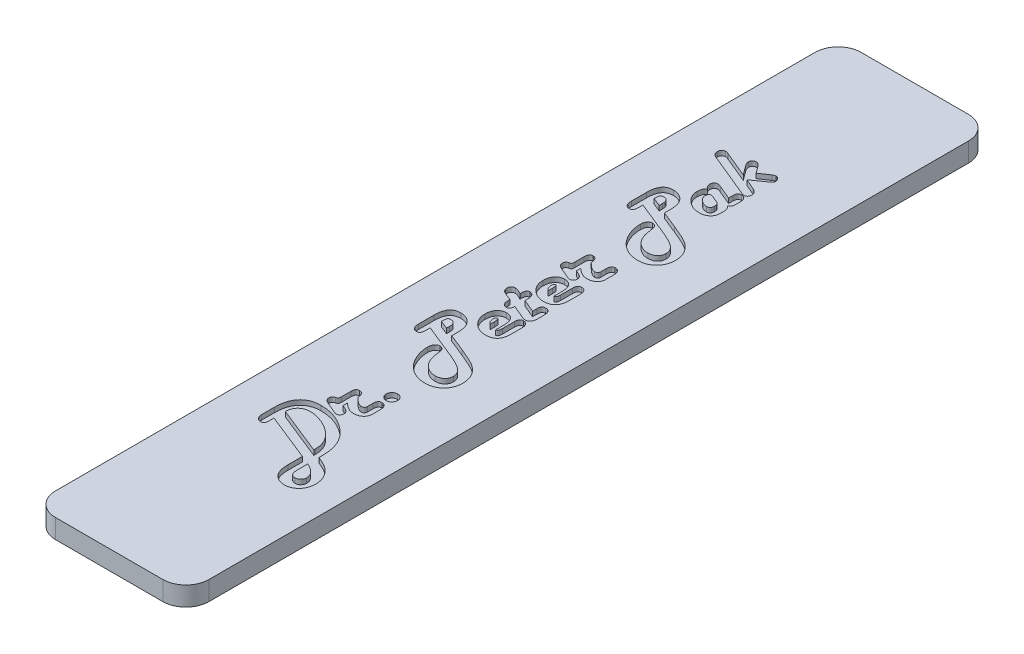
SolidWorks part; units mm, degrees
ref_plane "Front Plane" through (0, 0, 0) normal (0, 0, 1) x (1, 0, 0)
ref_plane "Top Plane" through (0, 0, 0) normal (0, 1, 0) x (1, 0, 0)
ref_plane "Right Plane" through (0, 0, 0) normal (1, 0, 0) x (0, 0, -1)
sketch "Sketch1" plane through (0, 0, 0) normal (0, 0, 1) x (1, 0, 0)
  line L0 (0, 1.5875) -> (0, -1.5875)
  line L1 (-12.7, 0) -> (12.7, 0) construction
  point P6 (0, 0)
  dimension "Width" = 25.4
  dimension "Thk" = 3.175
sketch "Sketch2" plane through (0, 0, 0) normal (1, 0, 0) x (0, 0, -1)
  line L0 (66.675, 0) -> (-66.675, 0)
  point P4 (0, 0)
  dimension "Length" = 133.35
sketch "Sketch3" plane through (0, 0, 0) normal (0, 0, 1) x (1, 0, 0)
  line L1 (12.7, 1.5875) -> (-12.7, 1.5875)
  line L2 (12.7, 1.5875) -> (12.7, -1.5875)
  line L3 (12.7, -1.5875) -> (-12.7, -1.5875)
  line L4 (-12.7, 1.5875) -> (-12.7, -1.5875)
  line L5 (12.7, 1.5875) -> (-12.7, -1.5875) construction
  line L6 (12.7, -1.5875) -> (-12.7, 1.5875) construction
  point P0 (0, 0)
extrude "Boss-Extrude1" add sketch "Sketch3" along normal up to vertex (66.675 mm away) and the other way up to vertex (66.675 mm away) up to point (0, 0, 66.675) other way up to point (0, 0, -66.675)
sketch "Sketch5" plane through (0, 1.5875, 0) normal (0, 1, 0) x (1, 0, 0)
  line L2 (9.652, -66.675) -> (-9.398, -66.675) construction
  line L3 (-12.7, -63.5025) -> (-12.7, 63.627) construction
  line L12 (12.7, -66.675) -> (12.7, 66.675)
  line L13 (12.7, 66.675) -> (-12.7, 66.675)
  line L14 (-12.7, 66.675) -> (-12.7, -66.675)
  line L15 (-12.7, -66.675) -> (12.7, -66.675)
  line L16 (12.7, -62.865) -> (12.7, 62.865)
  line L17 (8.89, 66.675) -> (-8.89, 66.675)
  line L18 (-12.7, 62.865) -> (-12.7, -62.865)
  line L19 (-8.89, -66.675) -> (8.89, -66.675)
  arc A8 (12.7, 62.865) -> (8.89, 66.675) centre (8.89, 62.865) ccw
  arc A9 (-8.89, 66.675) -> (-12.7, 62.865) centre (-8.89, 62.865) ccw
  arc A10 (12.7, -62.865) -> (8.89, -66.675) centre (8.89, -62.865) cw
  arc A11 (-8.89, -66.675) -> (-12.7, -62.865) centre (-8.89, -62.865) cw
  dimension "D2" = 3.81
  dimension "D1" = 0
extrude "Cut-Extrude2" cut sketch "Sketch5" against normal through all flip side to cut
sketch "Sketch4" plane through (0, 1.5875, 0) normal (0, 1, 0) x (1, 0, 0)
  line L0 (0, 0) -> (2.54, 0) construction
  line L1 (2.54, -66.675) -> (2.54, 66.675) construction
  line L2 (8.89, 66.675) -> (-8.89, 66.675) construction
  text T0 "Dr. Peter Pak" font "Harlow Solid Italic" height in points 36
  point P8 (2.54, 0)
  dimension "D1" = 2.54
extrude "Cut-Extrude1" cut sketch "Sketch4" against normal blind 0.7937
